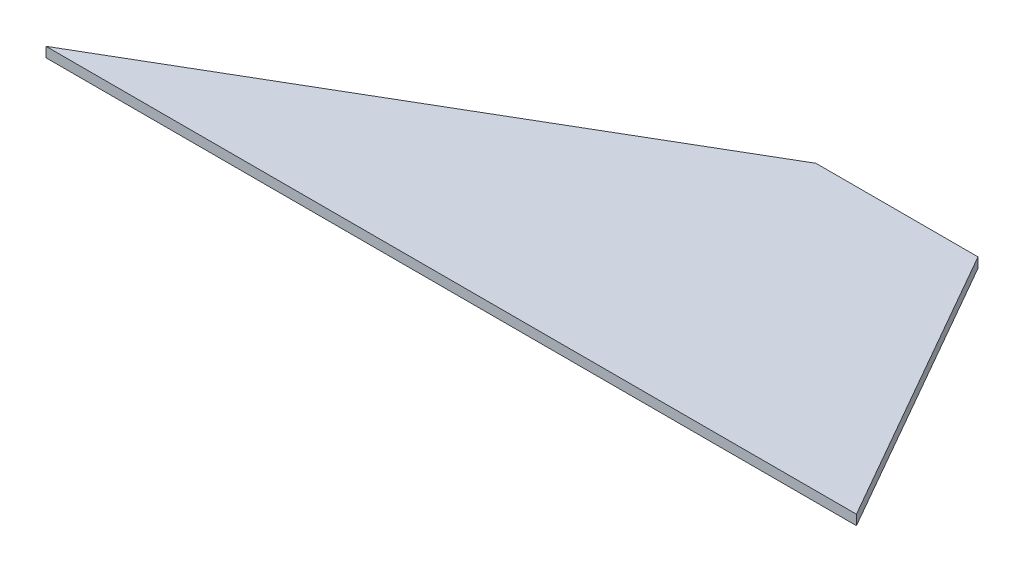
SolidWorks part; units mm, degrees
ref_plane "Front Plane" through (0, 0, 0) normal (0, 0, 1) x (1, 0, 0)
ref_plane "Top Plane" through (0, 0, 0) normal (0, 1, 0) x (1, 0, 0)
ref_plane "Right Plane" through (0, 0, 0) normal (1, 0, 0) x (0, 0, -1)
sketch "Sketch1" plane through (0, 0, 0) normal (0, 1, 0) x (1, 0, 0)
  line L0 (0, 0) -> (254, 0)
  line L1 (254, 0) -> (203.2, 88.9)
  line L2 (203.2, 88.9) -> (152.4, 88.9)
  line L3 (152.4, 88.9) -> (0, 0)
  dimension "D1" = 254
  dimension "D2" = 50.8
  dimension "D3" = 50.8
  dimension "D4" = 88.9
extrude "Boss-Extrude1" add sketch "Sketch1" along normal blind 3.1242
